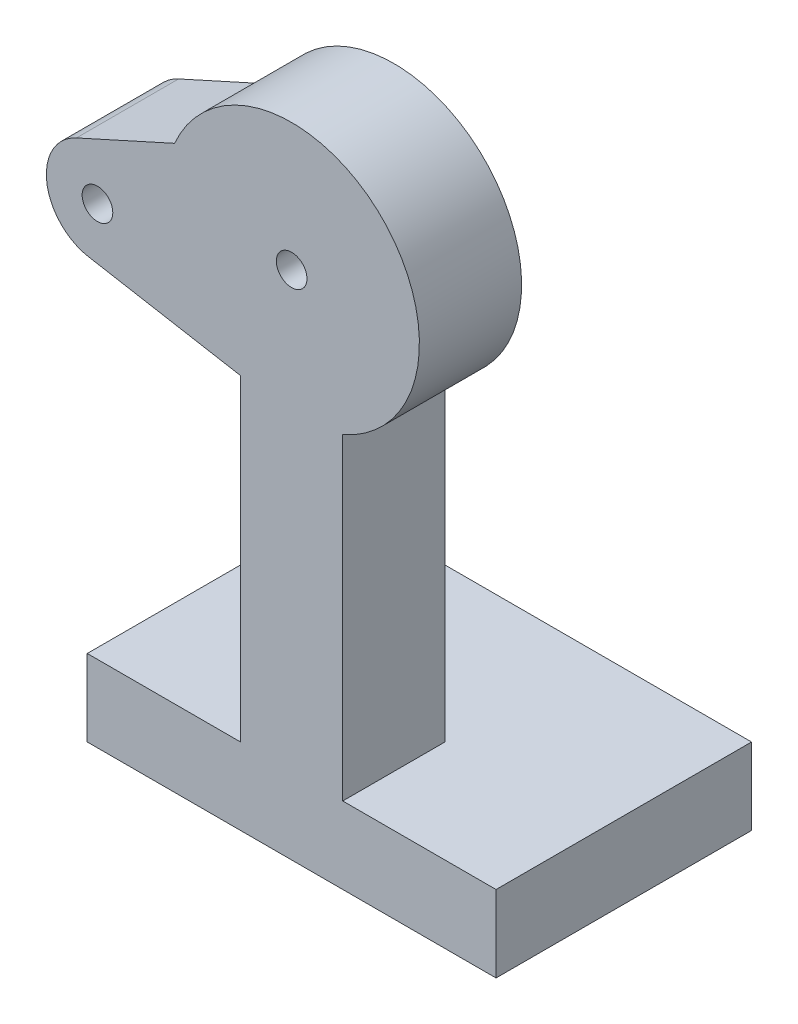
SolidWorks part; units mm, degrees
ref_plane "Front Plane" through (0, 0, 0) normal (0, 0, 1) x (1, 0, 0)
ref_plane "Top Plane" through (0, 0, 0) normal (0, 1, 0) x (1, 0, 0)
ref_plane "Right Plane" through (0, 0, 0) normal (1, 0, 0) x (0, 0, -1)
sketch "Sketch1" plane through (0, 0, 0) normal (0, 0, 1) x (1, 0, 0)
  line L0 (0, 0) -> (0, 246.3232) construction
  line L1 (-40, 7.5) -> (-10, 7.5)
  line L2 (-40, 7.5) -> (-40, -7.5)
  line L3 (-40, -7.5) -> (40, -7.5)
  line L4 (40, 7.5) -> (40, -7.5)
  line L5 (-40, 7.5) -> (40, -7.5) construction
  line L6 (-40, -7.5) -> (40, 7.5) construction
  line L8 (-10, 7.5) -> (-10, 69.5871)
  line L10 (10, 7.5) -> (10, 69.5871)
  line L11 (10, 7.5) -> (40, 7.5)
  arc A0 (10, 69.5871) -> (-10, 69.5871) centre (0, 92.5) ccw
  point P0 (0, 0)
  dimension "D4" = 25
  dimension "D5" = 100
  dimension "D1" = 15
  dimension "D2" = 80
  dimension "D3" = 20
extrude "Boss-Extrude1" add sketch "Sketch1" along normal mid plane 20 contours A0 L8 L1 L2 L3 L4 L11 L10
sketch "Sketch2" plane through (0, 0, 0) normal (0, 0, -1) x (-1, 0, 0)
  line L0 (-10, 7.5) -> (10, 7.5)
  line L7 (-10, 69.5871) -> (-10, 7.5)
  line L8 (-10, 7.5) -> (-40, 7.5)
  line L9 (-40, 7.5) -> (-40, -7.5)
  line L10 (-40, -7.5) -> (40, -7.5)
  line L11 (40, -7.5) -> (40, 7.5)
  line L12 (40, 7.5) -> (10, 7.5)
  line L13 (10, 7.5) -> (10, 69.5871)
  line L15 (-10, 7.5) -> (-40, 7.5)
  line L16 (-40, 7.5) -> (-40, -7.5)
  line L17 (-40, -7.5) -> (40, -7.5)
  line L18 (40, -7.5) -> (40, 7.5)
  line L19 (40, 7.5) -> (10, 7.5)
  arc A1 (10, 69.5871) -> (-10, 69.5871) centre (0, 92.5) ccw
  dimension "D1" = 0
extrude "Boss-Extrude2" add sketch "Sketch2" along normal blind 40
sketch "Sketch3" plane through (0, 0, 10) normal (0, 0, 1) x (1, 0, 0)
  circle A0 centre (0, 92.5) radius 3
  dimension "D1" = 6
extrude "Cut-Extrude1" cut sketch "Sketch3" against normal through all
sketch "Sketch4" plane through (0, 0, 10) normal (0, 0, 1) x (1, 0, 0)
  line L0 (-22.9129, 102.5) -> (-42.1214, 93.8112)
  line L1 (-10, 69.5871) -> (-39.7434, 74.8531)
  circle A0 centre (-38, 84.7) radius 3
  arc A1 (-42.1214, 93.8112) -> (-39.7434, 74.8531) centre (-38, 84.7) ccw
  arc A5 (10, 69.5871) -> (-10, 69.5871) centre (0, 92.5) ccw construction
  point P2 (0, 92.5)
  arc M3 (10, 69.5871) -> (-10, 69.5871) centre (0, 92.5) ccw
  dimension "D1" = 6
  dimension "D4" = 10
  dimension "D2" = 7.8
  dimension "D3" = 38
  dimension "D5" = 10
extrude "Boss-Extrude4" add sketch "Sketch4" against normal up to surface (20 mm away) contours L0 A1 L1 A0 M3 up to face at (3, 92.5, -10)
equation "\"positionscale\"= 1"
equation "\"D3@Sketch4\"= \"positionscale\" * 38.0"
equation "\"D2@Sketch4\"= \"positionscale\" * 7.80"
